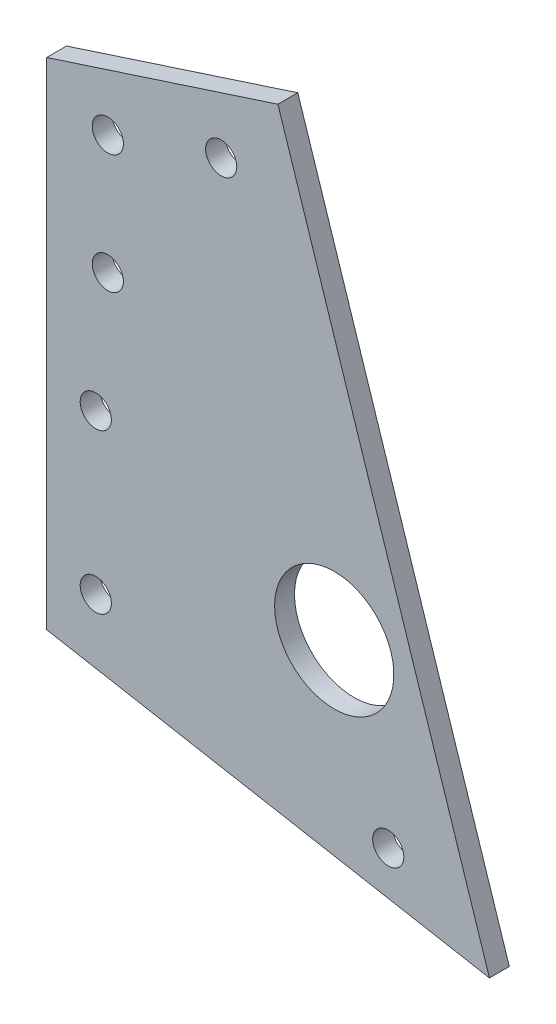
SolidWorks part; units mm, degrees
material "6061 Alloy"
ref_plane "Front Plane" through (0, 0, 0) normal (0, 0, 1) x (1, 0, 0)
ref_plane "Top Plane" through (0, 0, 0) normal (0, 1, 0) x (1, 0, 0)
ref_plane "Right Plane" through (0, 0, 0) normal (1, 0, 0) x (0, 0, -1)
sketch "Sketch2" plane through (0, 0, 0) normal (0, 0, 1) x (1, 0, 0)
  line L0 (40.9906, 297.6036) -> (41.8047, 295.0986) construction
  line L2 (40.9906, 297.6036) -> (52.5693, 261.9727) construction
  line L6 (197.5978, -184.3191) -> (40.9906, 297.6036) construction
  line L7 (75.6055, 191.0842) -> (41.8047, 295.0986)
  line L8 (4.8542, 283.091) -> (4.8542, 203.9015)
  line L9 (4.8542, 203.9015) -> (75.6055, 191.0842)
  line L10 (12.7, 238.125) -> (12.7, 212.725) construction
  line L11 (52.3134, 180.5741) -> (64.7523, 184.6158) construction
  line L12 (173.4413, -192.1691) -> (25.4, 263.394) construction
  line L13 (64.7523, 184.6158) -> (29.6, 292.8012) construction
  line L14 (41.8047, 295.0986) -> (4.8542, 283.091)
  dimension "D1" = 109.3686
extrude "Boss-Extrude1" add sketch "Sketch2" along normal blind 3.175
sketch "Sketch3" plane through (0, 0, 3.175) normal (0, 0, 1) x (1, 0, 0)
  line L0 (75.6055, 191.0842) -> (63.8877, 187.2769) construction
  line L1 (63.8877, 187.2769) -> (29.6006, 292.8015) construction
  line L3 (61.8403, 193.5779) -> (59.4352, 200.9803) construction
  line L4 (4.8542, 203.9015) -> (75.6055, 191.0842) construction
  line L5 (29.6006, 292.8015) -> (32.7403, 283.1387) construction
  line L6 (32.7403, 283.1387) -> (14.6226, 277.2519) construction
  line L7 (14.6226, 277.2519) -> (14.6226, 258.2019) construction
  dimension "D1" = 86.3865
hole_wizard "#10 Clearance Hole1" positions "Sketch4" profile "Sketch5" hole size "#10" standard "ANSI Inch" end condition through all
sketch "Sketch4" plane through (0, 0, 3.175) normal (0, 0, 1) x (1, 0, 0)
  point P0 (32.7403, 283.1387)
  point P3 (59.4352, 200.9803)
  point P7 (12.7, 238.125)
  point P10 (12.7, 212.725)
  point P14 (14.6226, 277.2519)
  point P17 (14.6226, 258.2019)
sketch "Sketch5" plane through (32.7403, 283.1387, 3.175) normal (1, 0, 0) x (0, -1, 0)
  line L0 (0, 0) -> (0, 3.175)
  line L1 (0, 3.175) -> (2.4892, 3.175)
  line L2 (2.4892, 3.175) -> (2.4892, 0)
  line L5 (2.4892, 0) -> (0, 0)
  line L11 (0, -6.35) -> (0, 107.95) construction
  dimension "Thru Hole Dia." = 4.9784
  dimension "Thru Hole Depth" = 3.175
sketch "Sketch8" plane through (0, 0, 0) normal (0, 0, -1) x (-1, 0, 0)
  circle A0 centre (-50.8, 225.425) radius 9.525
extrude "Cut-Extrude1" cut sketch "Sketch8" against normal through all
